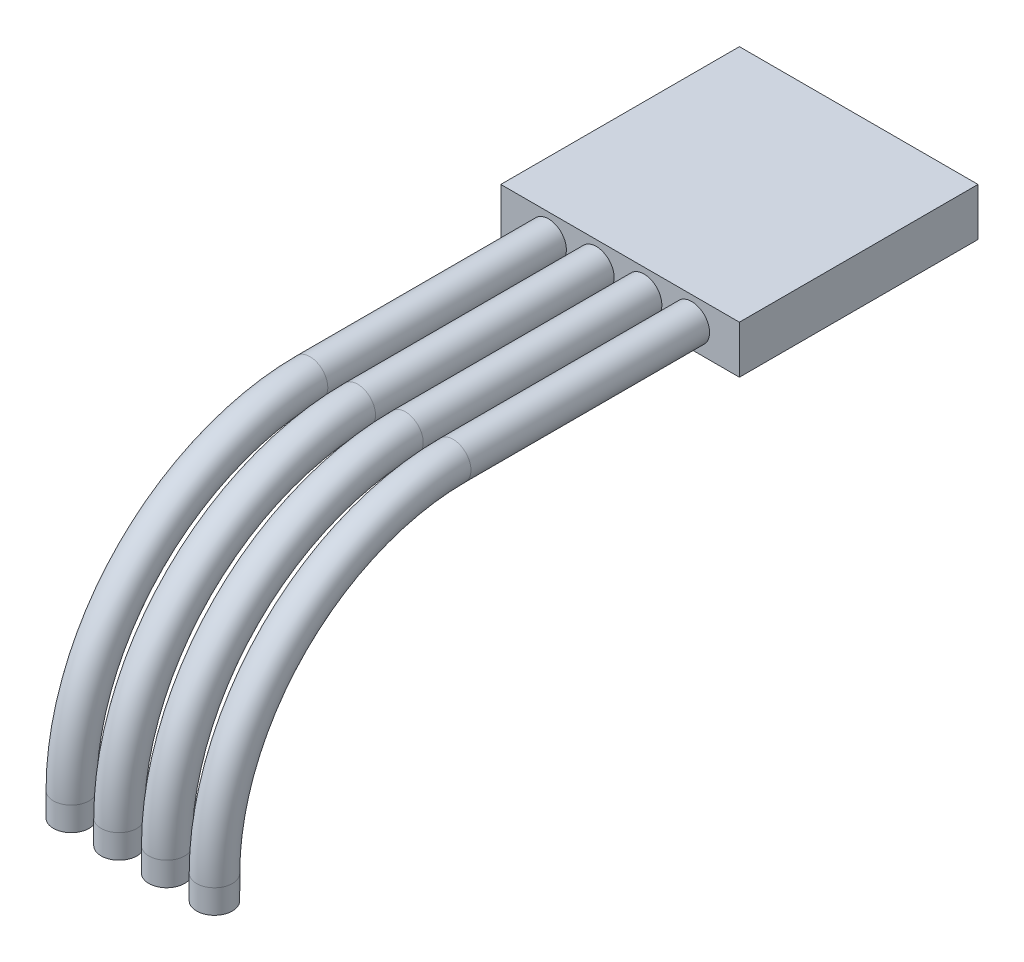
SolidWorks part; units mm, degrees
ref_plane "Ebene vorne" through (0, 0, 0) normal (0, 0, 1) x (1, 0, 0)
ref_plane "Ebene oben" through (0, 0, 0) normal (0, 1, 0) x (1, 0, 0)
ref_plane "Ebene rechts" through (0, 0, 0) normal (1, 0, 0) x (0, 0, -1)
sketch "Skizze1" plane through (0, 0, 0) normal (0, 0, 1) x (1, 0, 0)
  line L1 (-5, -1) -> (5, -1)
  line L2 (-5, -1) -> (-5, 1)
  line L3 (-5, 1) -> (5, 1)
  line L4 (5, -1) -> (5, 1)
  line L5 (-5, -1) -> (5, 1) construction
  line L6 (-5, 1) -> (5, -1) construction
  point P0 (0, 0)
  dimension "D1" = 10
  dimension "D2" = 2
extrude "Aufsatz-Linear austragen1" add sketch "Skizze1" along normal blind 10
sketch "Skizze2" plane through (0, 0, 10) normal (0, 0, 1) x (1, 0, 0)
  line L0 (0, 1) -> (0, -1) construction
  line L1 (5, 1) -> (-5, 1) construction
  line L2 (-5, -1) -> (5, -1) construction
  line L3 (0, 0) -> (-5.9149, 0) construction
  circle A0 centre (-1, 0) radius 0.75
  circle A1 centre (-3, 0) radius 0.75
  circle A2 centre (1, 0) radius 0.75
  circle A3 centre (3, 0) radius 0.75
  dimension "D1" = 1.5
  dimension "D2" = 1
  dimension "D3" = 2
extrude "Aufsatz-Linear austragen2" add sketch "Skizze2" along normal blind 10
ref_point "Punkt1"
ref_plane "Ebene1" through (-3, 0, 0) normal (1, 0, 0) x (0, 0, -1)
sketch "Skizze3" plane through (-3, 0, 0) normal (1, 0, 0) x (0, 0, -1)
  line L0 (-20, 0) -> (-20, -50000) construction
  line L1 (-30, -10) -> (-30, -11)
  arc A0 (-20, 0) -> (-30, -10) centre (-20, -10) ccw
  dimension "D1" = 10
  dimension "D2" = 1
sketch "Skizze4" plane through (0, 0, 20) normal (0, 0, 1) x (1, 0, 0)
  circle A1 centre (-3, 0) radius 0.75
  circle A2 centre (-3, 0) radius 0.75
  dimension "D1" = 0
sweep "Austragung1" add profiles "Skizze4" path "Skizze3"
pattern_linear "Lineares Muster1" count 4 spacing 2 along (1, 0, 0) of "Austragung1"
